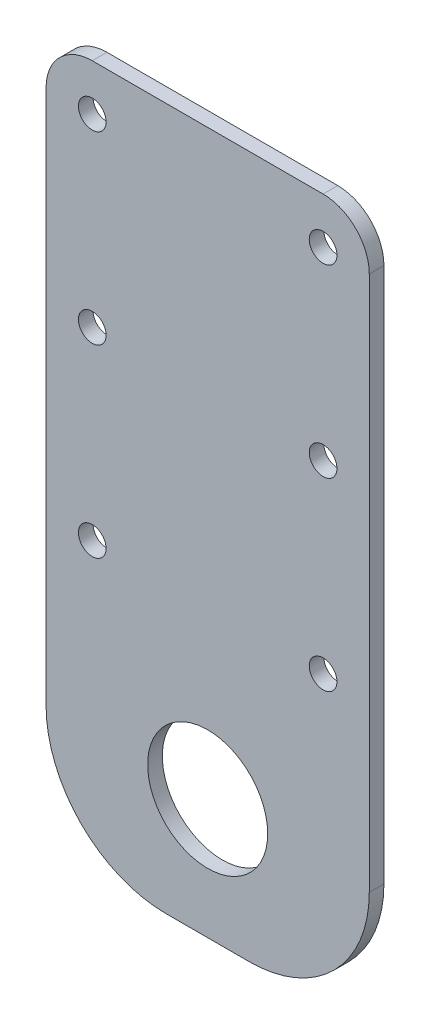
SolidWorks part; units mm, degrees
material "6061 Alloy"
ref_plane "Front Plane" through (0, 0, 0) normal (0, 0, 1) x (1, 0, 0)
ref_plane "Top Plane" through (0, 0, 0) normal (0, 1, 0) x (1, 0, 0)
ref_plane "Right Plane" through (0, 0, 0) normal (1, 0, 0) x (0, 0, -1)
sketch "Sketch1" plane through (0, 0, 0) normal (0, 0, 1) x (1, 0, 0)
  line L0 (0, 0) -> (0, 50)
  line L1 (0, 50) -> (35, 50)
  line L2 (35, 50) -> (35, 0)
  line L6 (0, 0) -> (35, 0) construction
  line L7 (5, 50) -> (5, 0) construction
  line L8 (0, 0) -> (5, 0) construction
  line L9 (5, 45) -> (5, 50) construction
  line L10 (17.5, 50) -> (17.5, -13) construction
  line L11 (0, 0) -> (0, -26)
  line L12 (0, -26) -> (35, -26)
  line L13 (0, 25) -> (5, 25) construction
  line L14 (35, -26) -> (35, 0)
  line L15 (17.5, -13) -> (17.5, 5) construction
  line L16 (17.5, 5) -> (30, 5) construction
  circle A0 centre (17.5, -13) radius 6.5
  circle A1 centre (5, 45) radius 1.5
  circle A2 centre (5, 25) radius 1.5
  circle A3 centre (5, 5) radius 1.5
  circle A4 centre (30, 5) radius 1.5
  circle A5 centre (30, 25) radius 1.5
  circle A6 centre (30, 45) radius 1.5
  dimension "D5" = 13
  dimension "D7" = 3
  dimension "D9" = 20
  dimension "D10" = 20
  dimension "D1" = 35
  dimension "D2" = 50
  dimension "D3" = 13
  dimension "D4" = 13
  dimension "D6" = 5
  dimension "D8" = 5
extrude "Boss-Extrude1" add sketch "Sketch1" along normal blind 1.5875
fillet "Fillet1" radius 5 2 edges at (0, 50, 0.7937) (35, 50, 0.7937)
fillet "Fillet2" radius 13 2 edges at (35, -26, 0.7937) (0, -26, 0.7937)
